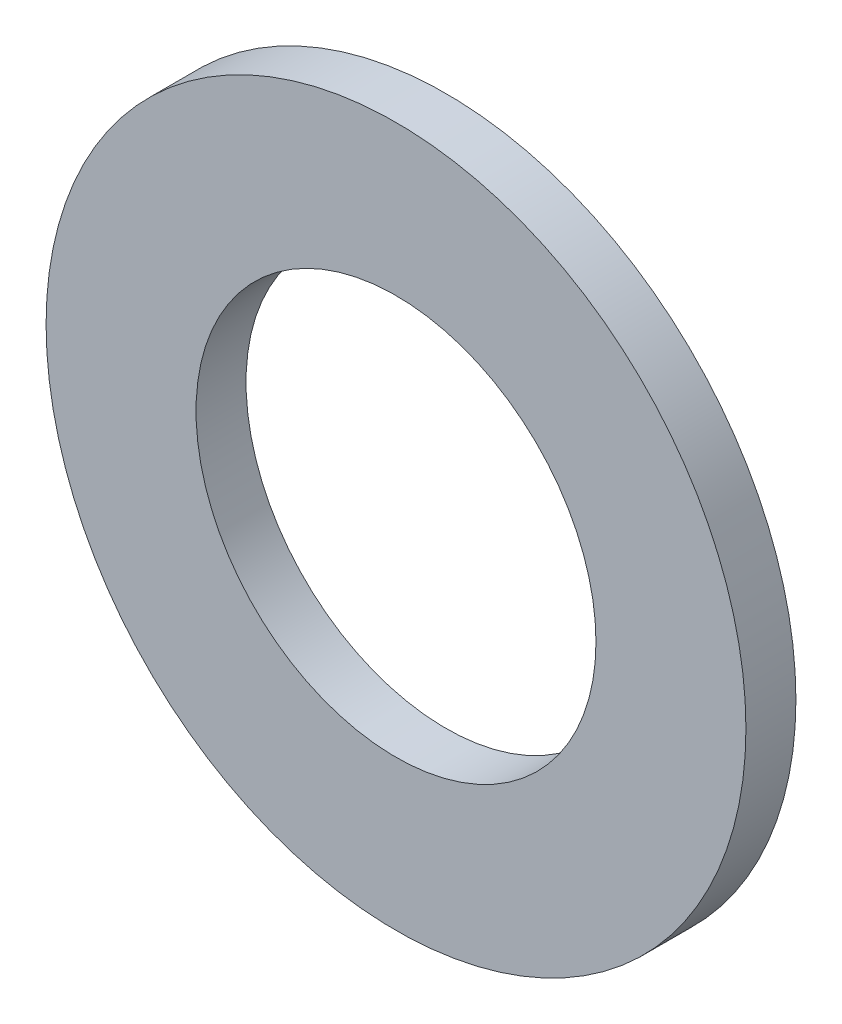
SolidWorks part; units mm, degrees
material "AISI 304"
ref_plane "前视基准面" through (0, 0, 0) normal (0, 0, 1) x (1, 0, 0)
ref_plane "上视基准面" through (0, 0, 0) normal (0, 1, 0) x (1, 0, 0)
ref_plane "右视基准面" through (0, 0, 0) normal (1, 0, 0) x (0, 0, -1)
other "Configuration Table"
sketch "草图1" plane through (0, 0, 0) normal (0, 0, 1) x (1, 0, 0)
  circle A0 centre (0, 0) radius 3.5
  circle A1 centre (0, 0) radius 2
  dimension "D1" = 7
  dimension "D2" = 4
extrude "凸台-拉伸1" add sketch "草图1" along normal blind 0.5
